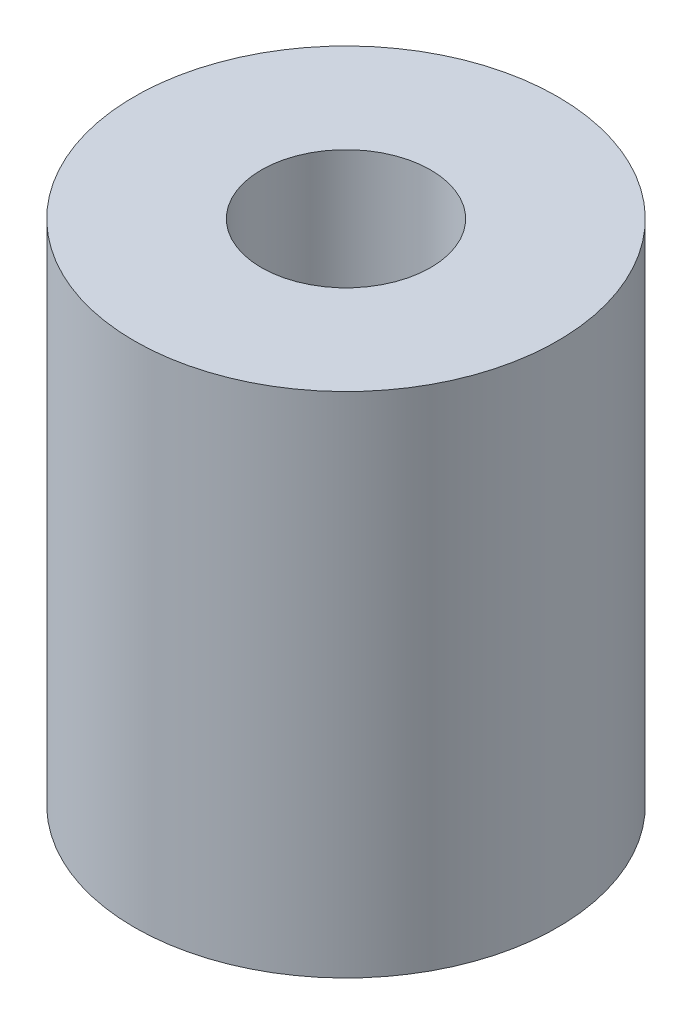
SolidWorks part; units mm, degrees
ref_plane "Front Plane" through (0, 0, 0) normal (0, 0, 1) x (1, 0, 0)
ref_plane "Top Plane" through (0, 0, 0) normal (0, 1, 0) x (1, 0, 0)
ref_plane "Right Plane" through (0, 0, 0) normal (1, 0, 0) x (0, 0, -1)
sketch "Sketch1" plane through (0, 0, 0) normal (0, 1, 0) x (1, 0, 0)
  circle A0 centre (0, 0) radius 12.5
  dimension "D1" = 25
extrude "Boss-Extrude1" add sketch "Sketch1" along normal blind 30
hole_wizard "Ø10.0 (10) Diameter Hole1" positions "Sketch3" profile "Sketch2" hole size "Ø10.0" standard "ISO"
sketch "Sketch3" plane through (0, 30, 0) normal (0, 1, 0) x (1, 0, 0)
  point P0 (0, 0)
sketch "Sketch2" plane through (0, 30, 0) normal (1, 0, 0) x (0, 0, 1)
  line L0 (0, 0) -> (0, 18.0043)
  line L1 (0, 18.0043) -> (5, 15)
  line L2 (5, 15) -> (5, 0)
  line L5 (5, 0) -> (0, 0)
  line L10 (0, 18.0043) -> (-5, 15) construction
  line L11 (0, -6.35) -> (0, 107.95) construction
  dimension "Hole Dia." = 10
  dimension "Hole Depth" = 15
  dimension "Drill Angle" = 118
hole_wizard "Ø8.0 (8) Diameter Hole1" positions "Sketch5" profile "Sketch4" hole size "Ø8.0" standard "ISO"
sketch "Sketch5" plane through (0, 0, 0) normal (0, -1, 0) x (-1, 0, 0)
  point P0 (0, 0)
sketch "Sketch4" plane through (0, 0, 0) normal (1, 0, 0) x (0, 0, -1)
  line L0 (0, 0) -> (0, 17.4034)
  line L1 (0, 17.4034) -> (4, 15)
  line L2 (4, 15) -> (4, 0)
  line L5 (4, 0) -> (0, 0)
  line L10 (0, 17.4034) -> (-4, 15) construction
  line L11 (0, -6.35) -> (0, 107.95) construction
  dimension "Hole Dia." = 8
  dimension "Hole Depth" = 15
  dimension "Drill Angle" = 118
